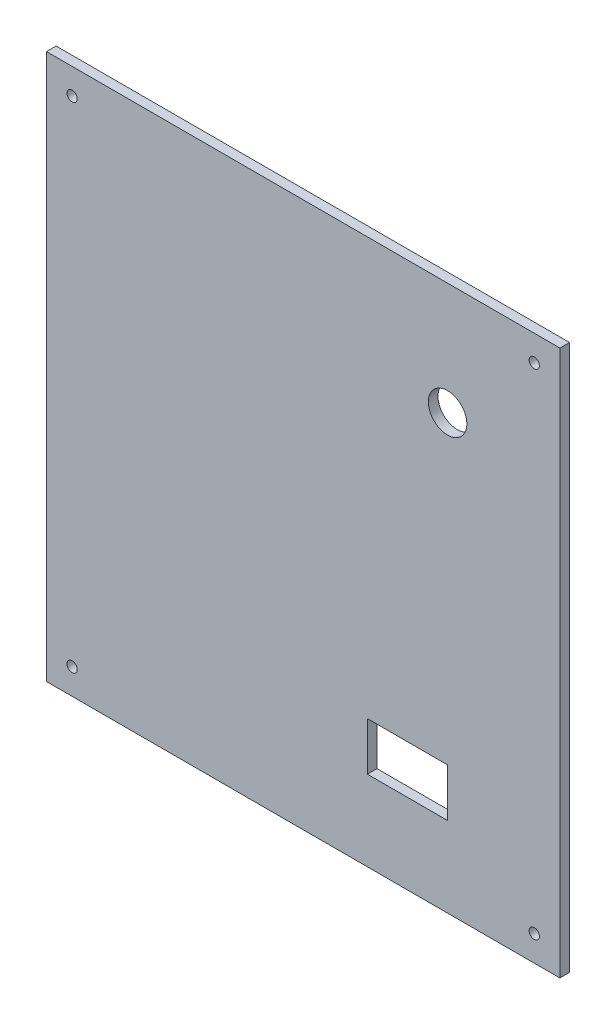
SolidWorks part; units mm, degrees
ref_plane "前视基准面" through (0, 0, 0) normal (0, 0, 1) x (1, 0, 0)
ref_plane "上视基准面" through (0, 0, 0) normal (0, 1, 0) x (1, 0, 0)
ref_plane "右视基准面" through (0, 0, 0) normal (1, 0, 0) x (0, 0, -1)
sketch "草图1" plane through (0, 0, 0) normal (0, 0, 1) x (1, 0, 0)
  line L1 (-44.5833, 38.75) -> (115.4167, 38.75)
  line L2 (-44.5833, 38.75) -> (-44.5833, -131.25)
  line L3 (-44.5833, -131.25) -> (115.4167, -131.25)
  line L4 (115.4167, 38.75) -> (115.4167, -131.25)
  dimension "D1" = 160
  dimension "D2" = 170
extrude "凸台-拉伸1" add sketch "草图1" along normal blind 3
sketch "草图2" plane through (0, 0, 3) normal (0, 0, 1) x (1, 0, 0)
  line L0 (35.4167, 44.6573) -> (35.4167, -142.6669) construction
  line L1 (-77.9879, -46.25) -> (146.9848, -46.25) construction
  line L2 (115.4167, 38.75) -> (-44.5833, 38.75) construction
  line L5 (-44.5833, -131.25) -> (115.4167, -131.25) construction
  line L6 (-44.5833, 38.75) -> (-44.5833, -131.25) construction
  line L7 (115.4167, -131.25) -> (115.4167, 38.75) construction
  circle A0 centre (-36.5833, 30.75) radius 1.6
  circle A2 centre (107.4167, 30.75) radius 1.6
  circle A3 centre (107.4167, -123.25) radius 1.6
  circle A4 centre (-36.5833, -123.25) radius 1.6
  point P12 (0, 0)
  dimension "D5" = 3.2
  dimension "D6" = 8
  dimension "D1" = 85
  dimension "D2" = 85
  dimension "D3" = 80
  dimension "D4" = 80
  dimension "D7" = 8
extrude "切除-拉伸1" cut sketch "草图2" against normal blind 13
sketch "草图3" plane through (0, 0, 3) normal (0, 0, 1) x (1, 0, 0)
  line L0 (115.4167, -131.25) -> (115.4167, 38.75) construction
  line L1 (115.4167, 38.75) -> (-44.5833, 38.75) construction
  circle A0 centre (80.4167, 3.75) radius 6
  dimension "D1" = 12
  dimension "D2" = 35
  dimension "D3" = 35
extrude "切除-拉伸2" cut sketch "草图3" against normal blind 13
sketch "草图4" plane through (0, 0, 3) normal (0, 0, 1) x (1, 0, 0)
  line L0 (115.4167, -131.25) -> (115.4167, 38.75) construction
  line L1 (55.4167, -91.25) -> (80.4167, -91.25)
  line L2 (55.4167, -91.25) -> (55.4167, -106.25)
  line L3 (55.4167, -106.25) -> (80.4167, -106.25)
  line L4 (80.4167, -91.25) -> (80.4167, -106.25)
  line L5 (-44.5833, -131.25) -> (115.4167, -131.25) construction
  dimension "D1" = 25
  dimension "D2" = 15
  dimension "D3" = 35
  dimension "D4" = 25
extrude "切除-拉伸3" cut sketch "草图4" against normal blind 13
